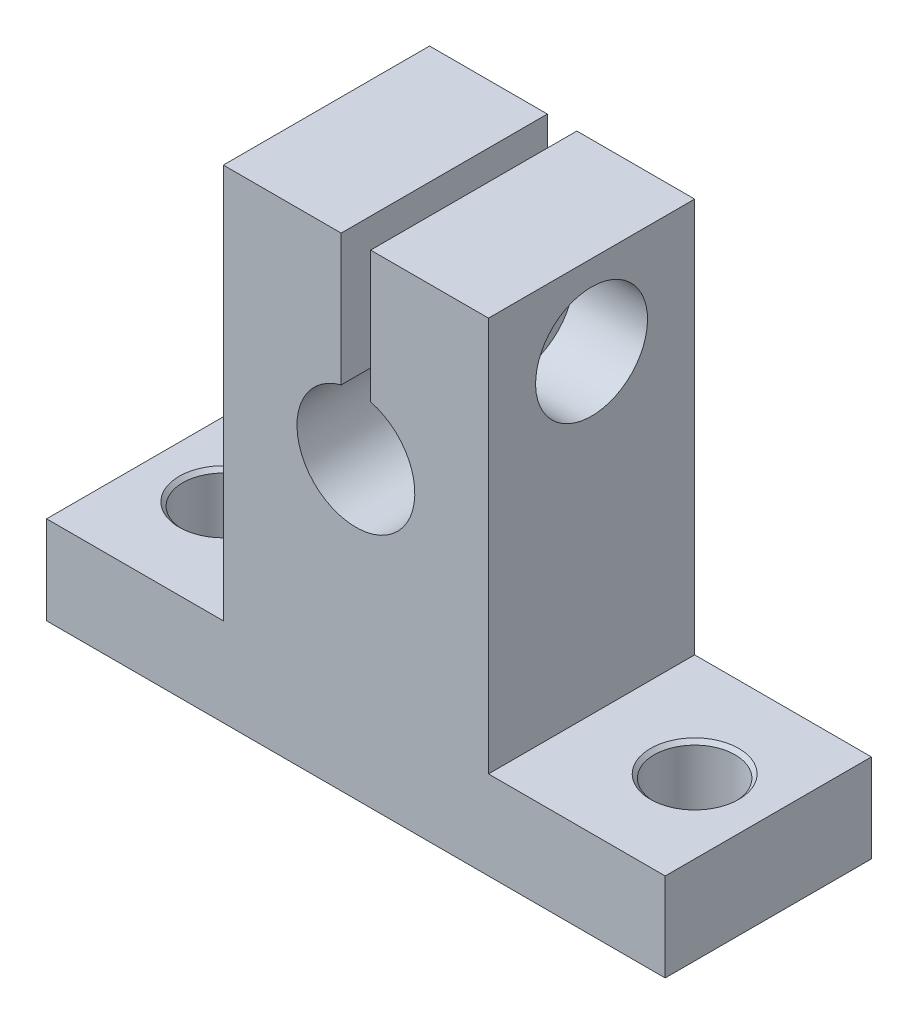
SolidWorks part; units mm, degrees
material "Д16Т ГОСТ 4784-97"
ref_plane "Спереди" through (0, 0, 0) normal (0, 0, 1) x (1, 0, 0)
ref_plane "Сверху" through (0, 0, 0) normal (0, 1, 0) x (1, 0, 0)
ref_plane "Справа" through (0, 0, 0) normal (1, 0, 0) x (0, 0, -1)
sketch "Эскиз1" plane through (0, 0, 0) normal (0, 0, 1) x (1, 0, 0)
  line L0 (-9, 16.4) -> (-1, 16.4)
  line L1 (-1, 16.4) -> (-1, 7.473)
  line L2 (1, 7.473) -> (1, 16.4)
  line L3 (1, 16.4) -> (9, 16.4)
  line L4 (9, 16.4) -> (9, -10.4)
  line L5 (9, -10.4) -> (21, -10.4)
  line L6 (21, -10.4) -> (21, -16.4)
  line L7 (21, -16.4) -> (-21, -16.4)
  line L8 (-21, -16.4) -> (-21, -10.4)
  line L9 (-21, -10.4) -> (-9, -10.4)
  line L10 (-9, -10.4) -> (-9, 16.4)
  line L11 (-1, 16.4) -> (1, 16.4) construction
  line L12 (0, 16.4) -> (0, -16.4) construction
  arc A0 (-1, 7.473) -> (1, 7.473) centre (0, 3.6) ccw
  point P16 (0, 0)
  dimension "D2" = 20
  dimension "D" = 8
  dimension "D1" = 2
  dimension "E" = 18
  dimension "H" = 32.8
  dimension "G" = 6
  dimension "W" = 42
extrude "Бобышка-Вытянуть1" add sketch "Эскиз1" along normal mid plane 14
sketch "Эскиз2" plane through (0, -10.4, 0) normal (0, 1, 0) x (1, 0, 0)
  line L0 (-16, 0) -> (16, 0) construction
  circle A0 centre (-16, 0) radius 2.75
  circle A1 centre (16, 0) radius 2.75
  dimension "S" = 5.5
  dimension "C" = 32
extrude "Вырез-Вытянуть1" cut sketch "Эскиз2" against normal up to surface (6 mm away) up to face at (0, -16.4, 0)
sketch "Эскиз4" plane through (-1, 0, 0) normal (1, 0, 0) x (0, 0, -1)
  line L0 (-7, 11.9365) -> (7, 11.9365) construction
  line L2 (-7, 7.473) -> (-7, 16.4) construction
  line L3 (7, 7.473) -> (7, 16.4) construction
  circle A0 centre (0, 10.9365) radius 1.65
  dimension "D1" = 1
  dimension "dM" = 3.3
extrude "Вырез-Вытянуть2" cut sketch "Эскиз4" against normal up to surface (8 mm away) up to face at (-9, 3, 0)
cosmetic thread "Условное изображение резьбы1" parameters "D2"=4
sketch "Эскиз5" plane through (9, 0, 0) normal (1, 0, 0) x (0, 0, -1)
  circle A0 centre (0, 10.9365) radius 2.1
  dimension "dM1" = 4.2
extrude "Вырез-Вытянуть3" cut sketch "Эскиз5" against normal up to surface (8 mm away) up to face at (1, 11.9365, 0)
sketch "Эскиз6" plane through (9, 0, 0) normal (1, 0, 0) x (0, 0, -1)
  circle A0 centre (0, 10.9365) radius 3.8
  dimension "dV" = 7.6
extrude "Вырез-Вытянуть4" cut sketch "Эскиз6" against normal blind 5
chamfer "Фаска1" distance 0.25 angle 45 3 edges at (13.25, -10.4, 0) (-18.75, -10.4, 0) (-9, 12.5865, 0)
